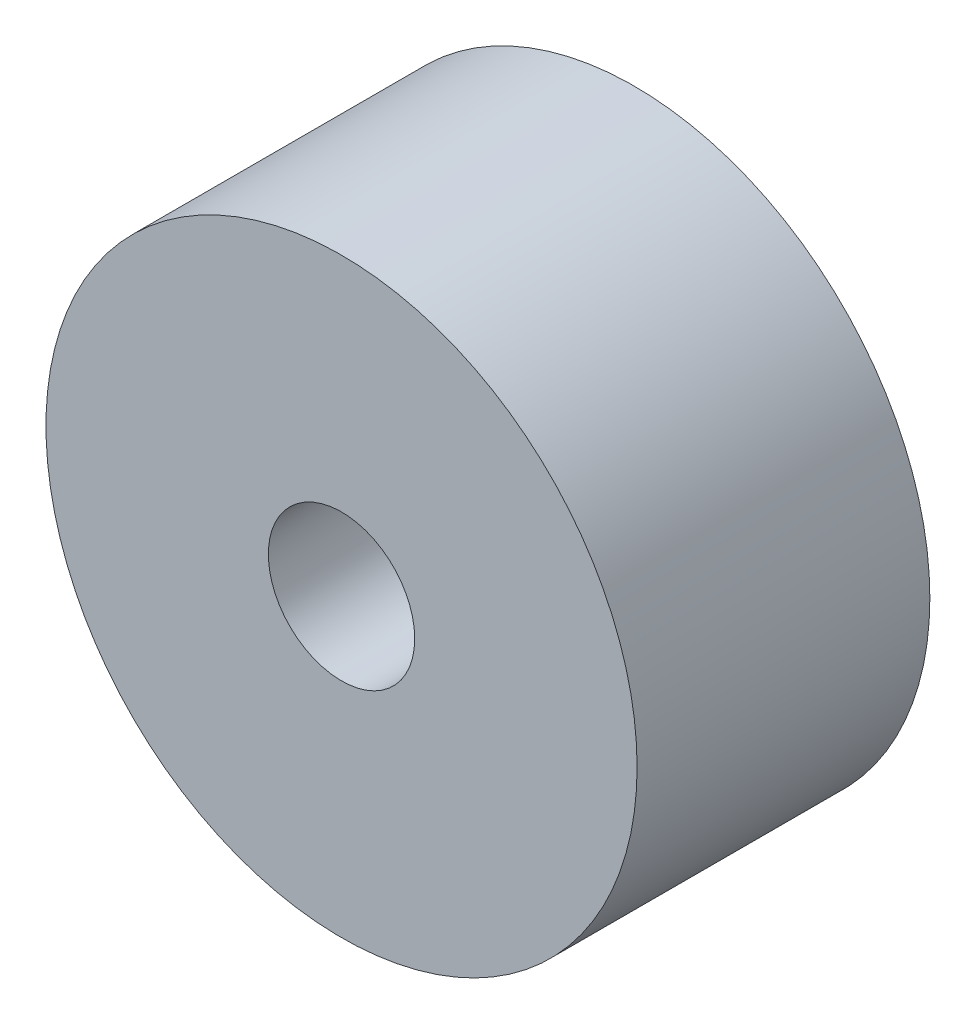
SolidWorks part; units mm, degrees
ref_plane "Спереди" through (0, 0, 0) normal (0, 0, 1) x (1, 0, 0)
ref_plane "Сверху" through (0, 0, 0) normal (0, 1, 0) x (1, 0, 0)
ref_plane "Справа" through (0, 0, 0) normal (1, 0, 0) x (0, 0, -1)
sketch "Эскиз1" plane through (0, 0, 0) normal (0, 0, 1) x (1, 0, 0)
  circle A0 centre (0, 0) radius 40.3846
  circle A1 centre (0, 0) radius 10
extrude "Carrier" add sketch "Эскиз1" along normal blind 40 from offset 20
